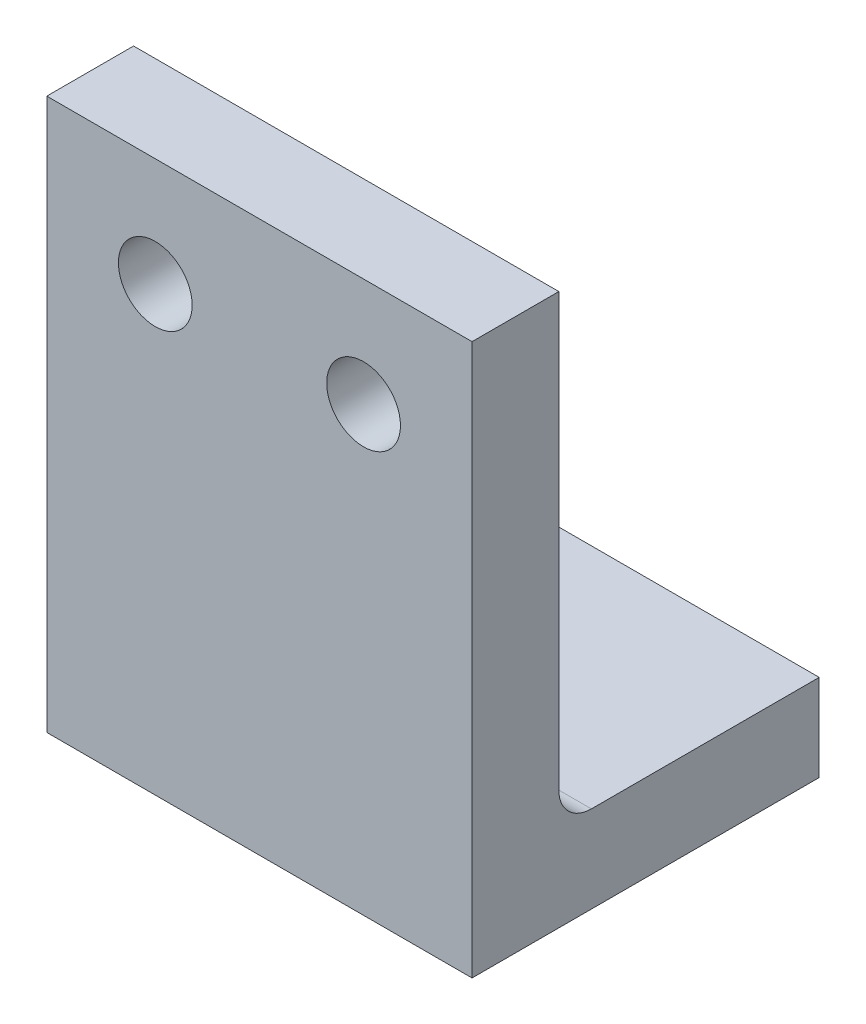
SolidWorks part; units mm, degrees
ref_plane "Front Plane" through (0, 0, 0) normal (0, 0, 1) x (1, 0, 0)
ref_plane "Top Plane" through (0, 0, 0) normal (0, 1, 0) x (1, 0, 0)
ref_plane "Right Plane" through (0, 0, 0) normal (1, 0, 0) x (0, 0, -1)
sketch "Sketch1" plane through (0, 0, 0) normal (0, 0, 1) x (1, 0, 0)
  line L0 (-4.8, 0) -> (4.8, 0) construction
  line L2 (-9.8, 5) -> (9.8, 5)
  line L3 (-9.8, 5) -> (-9.8, -16.4)
  line L4 (-9.8, -16.4) -> (9.8, -16.4)
  line L5 (9.8, 5) -> (9.8, -16.4)
  circle A0 centre (-4.8, 0) radius 1.7
  circle A1 centre (4.8, 0) radius 1.7
  point P4 (0, 0)
  point P10 (0, 5)
  dimension "D1" = 3.4
  dimension "D2" = 9.6
  dimension "D3" = 16.4
  dimension "D4" = 5
  dimension "D5" = 5
extrude "Boss-Extrude1" add sketch "Sketch1" along normal blind 4
sketch "Sketch3" plane through (0, -16.4, 0) normal (0, -1, 0) x (1, 0, 0)
  line L0 (9.8, 4) -> (9.8, 0) construction
  line L1 (-9.8, 4) -> (9.8, 4)
  line L2 (-9.8, 4) -> (-9.8, -12)
  line L3 (-9.8, -12) -> (9.8, -12)
  line L4 (9.8, 4) -> (9.8, -12)
  dimension "D1" = 16
extrude "Boss-Extrude2" add sketch "Sketch3" along normal blind 4
fillet "Fillet1" radius 1.5 1 edges at (0, -16.4, 0)
equation "\"paddin\"=5"
equation "\"D4@Sketch1\"=\"paddin\""
equation "\"D5@Sketch1\"=\"paddin\""
